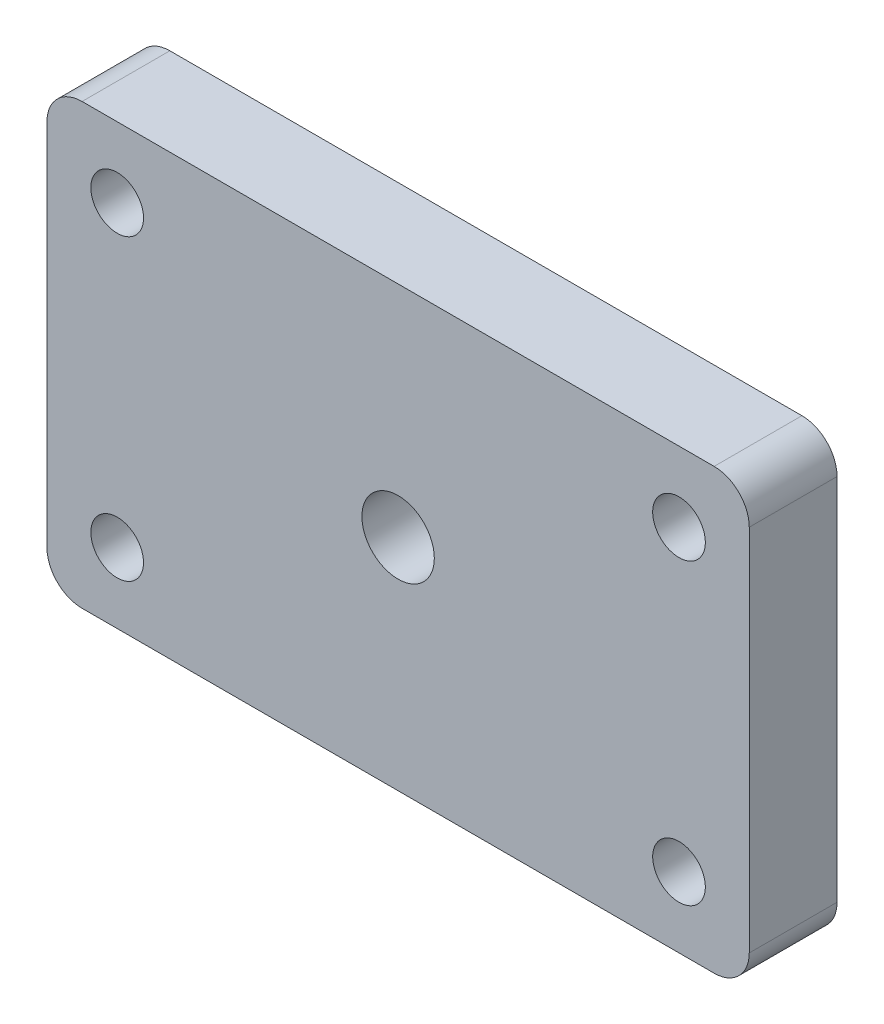
SolidWorks part; units mm, degrees
ref_plane "Front Plane" through (0, 0, 0) normal (0, 0, 1) x (1, 0, 0)
ref_plane "Top Plane" through (0, 0, 0) normal (0, 1, 0) x (1, 0, 0)
ref_plane "Right Plane" through (0, 0, 0) normal (1, 0, 0) x (0, 0, -1)
sketch "Model" plane through (0, 0, 0) normal (0, 0, 1) x (1, 0, 0)
  line L0 (36, -25) -> (-36, -25)
  line L1 (40, 21) -> (40, -21)
  line L2 (-36, 25) -> (36, 25)
  line L3 (-40, -21) -> (-40, 21)
  circle A0 centre (32, 17) radius 3
  circle A1 centre (-32, 17) radius 3
  circle A2 centre (32, -17) radius 3
  circle A3 centre (0, 0) radius 4.125
  circle A4 centre (-32, -17) radius 3
  arc A5 (-36, 25) -> (-40, 21) centre (-36, 21) ccw
  arc A6 (40, 21) -> (36, 25) centre (36, 21) ccw
  arc A7 (36, -25) -> (40, -21) centre (36, -21) ccw
  arc A8 (-40, -21) -> (-36, -25) centre (-36, -21) ccw
extrude "Boss-Extrude1" add sketch "Model" along normal blind 10
sketch "Sketch2" plane through (0, 0, 10) normal (0, 0, 1) x (1, 0, 0)
  text T0 "Copyright © Adarsh Belavatagi and Manikanta Pujar 2018.\r\nThis documentation describes Open Hardware and is licensed under the CERN OHL v. 1.2.\r\nYou may redistribute and modify this documentation under the terms of the CERN OHL v.1.2.\r\n(http://ohwr.org/cernohl). This documentation is distributed WITHOUT ANY EXPRESS OR\r\nIMPLIED WARRANTY, INCLUDING OF MERCHANTABILITY, SATISFACTORY QUALITY AND FITNESS FOR A PARTICULAR PURPOSE.\r\nPlease see the CERN OHL v.1.2 for applicable conditions\r\n\r\nThe full text of the license is available in LICENSE.txt(https://github.com/AdarshBelavatagi/Maudslay/blob/master/LICENSE.txt)"
